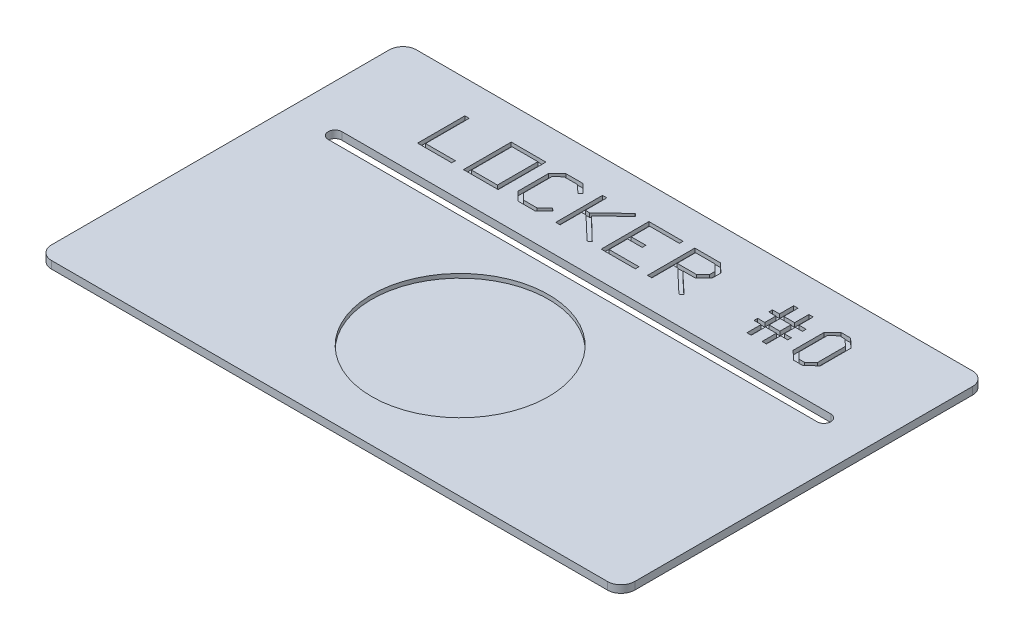
SolidWorks part; units mm, degrees
ref_plane "Спереди" through (0, 0, 0) normal (0, 0, 1) x (1, 0, 0)
ref_plane "Сверху" through (0, 0, 0) normal (0, 1, 0) x (1, 0, 0)
ref_plane "Справа" through (0, 0, 0) normal (1, 0, 0) x (0, 0, -1)
sketch "Эскиз1" plane through (0, 0, 0) normal (0, 1, 0) x (1, 0, 0)
  line L1 (-40.75, 26.75) -> (40.75, 26.75)
  line L2 (-42.75, 24.75) -> (-42.75, -24.75)
  line L3 (-40.75, -26.75) -> (40.75, -26.75)
  line L4 (42.75, 24.75) -> (42.75, -24.75)
  line L5 (-42.75, 26.75) -> (42.75, -26.75) construction
  line L6 (-42.75, -26.75) -> (42.75, 26.75) construction
  arc A0 (-42.75, -24.75) -> (-40.75, -26.75) centre (-40.75, -24.75) ccw
  arc A1 (40.75, -26.75) -> (42.75, -24.75) centre (40.75, -24.75) ccw
  arc A2 (42.75, 24.75) -> (40.75, 26.75) centre (40.75, 24.75) ccw
  arc A3 (-40.75, 26.75) -> (-42.75, 24.75) centre (-40.75, 24.75) ccw
  point P0 (0, 0)
  dimension "D3" = 2
  dimension "D1" = 85.5
  dimension "D2" = 53.5
extrude "Бобышка-Вытянуть1" add sketch "Эскиз1" along normal blind 1.1
sketch "Эскиз4" plane through (0, 1.1, 0) normal (0, 1, 0) x (1, 0, 0)
  circle A0 centre (0, -7.6031) radius 12.96
  text T0 "LOCKER #0" font "Txt_IV25" height 7
extrude "Вырез-Вытянуть8" cut sketch "Эскиз4" against normal blind 0.6
sketch "Эскиз5" plane through (0, 1.1, 0) normal (0, 1, 0) x (1, 0, 0)
  line L1 (-35.8453, 10.8978) -> (35.8453, 10.8978)
  line L3 (-35.8453, 8.8978) -> (35.8453, 8.8978)
  line L5 (-36.8453, 10.8978) -> (36.8453, 8.8978) construction
  line L6 (-36.8453, 8.8978) -> (36.8453, 10.8978) construction
  arc A1 (-35.8453, 10.8978) -> (-35.8453, 8.8978) centre (-35.8453, 9.8978) ccw
  arc A3 (35.8453, 8.8978) -> (35.8453, 10.8978) centre (35.8453, 9.8978) ccw
  point P0 (0, 9.8978)
extrude "Вырез-Вытянуть9" cut sketch "Эскиз5" against normal through all
